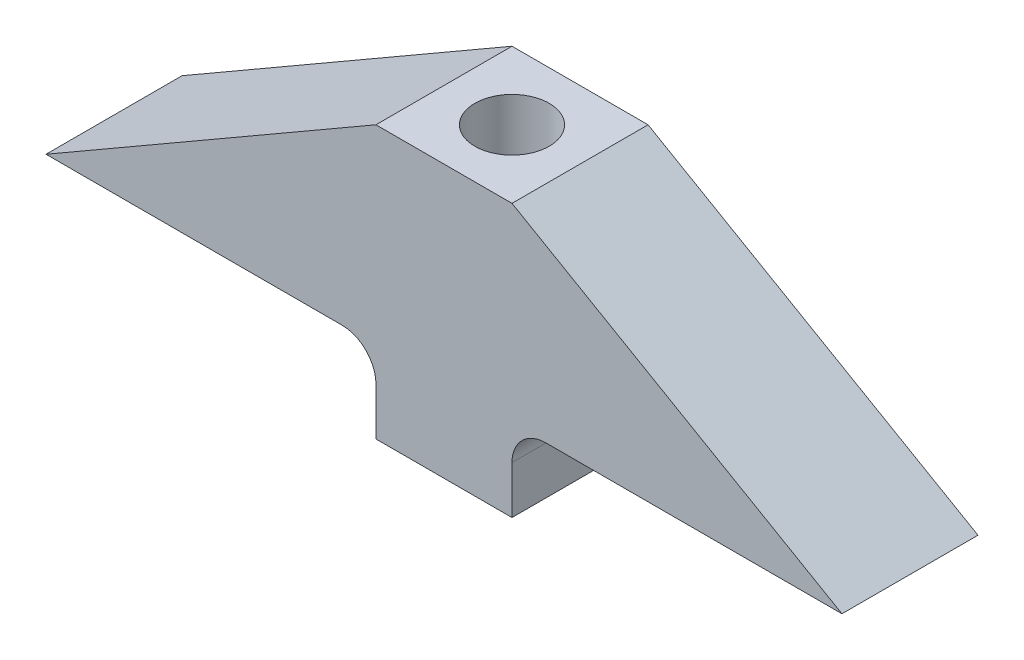
SolidWorks part; units mm, degrees
material "6061-T6 (SS)"
ref_plane "Front Plane" through (0, 0, 0) normal (0, 0, 1) x (1, 0, 0)
ref_plane "Top Plane" through (0, 0, 0) normal (0, 1, 0) x (1, 0, 0)
ref_plane "Right Plane" through (0, 0, 0) normal (1, 0, 0) x (0, 0, -1)
sketch "Sketch1" plane through (0, 0, 0) normal (0, 0, 1) x (1, 0, 0)
  line L0 (0, 0) -> (61.5917, 0)
  line L1 (148.5835, 0) -> (86.9917, 35.56)
  line L2 (86.9917, 35.56) -> (61.5917, 35.56)
  line L3 (61.5917, 35.56) -> (0, 0)
  line L4 (61.5917, 0) -> (61.5917, -15.24)
  line L5 (61.5917, -15.24) -> (86.9917, -15.24)
  line L6 (86.9917, -15.24) -> (86.9917, 0)
  line L7 (86.9917, 0) -> (148.5835, 0)
  point P8 (74.2917, -15.24)
  point P10 (74.2917, 35.56)
  dimension "D1" = 30
  dimension "D2" = 30
  dimension "D3" = 25.4
  dimension "D4" = 35.56
  dimension "D5" = 50.8
  dimension "D6" = 25.4
extrude "Boss-Extrude1" add sketch "Sketch1" along normal blind 25.4
hole_wizard "35/64 (0.54688) Diameter Hole1" positions "Sketch2" profile "Sketch3" hole size "35/64" standard "ANSI Inch"
sketch "Sketch2" plane through (0, 35.56, 0) normal (0, 1, 0) x (1, 0, 0)
  point P0 (74.2917, -12.7)
  dimension "D1" = 12.7
  dimension "D2" = 12.7
sketch "Sketch3" plane through (74.2917, 35.56, 12.7) normal (1, 0, 0) x (0, 0, 1)
  line L0 (0, 0) -> (0, 39.2252)
  line L1 (0, 39.2252) -> (6.9454, 35.052)
  line L2 (6.9454, 35.052) -> (6.9454, 0)
  line L5 (6.9454, 0) -> (0, 0)
  line L10 (0, 39.2252) -> (-6.9454, 35.052) construction
  line L11 (0, -6.35) -> (0, 107.95) construction
  dimension "Hole Dia." = 13.8908
  dimension "Hole Depth" = 35.052
  dimension "Drill Angle" = 118
hole_wizard "#10-32 Tapped Hole1" positions "Sketch4" profile "Sketch5" tap size "#10-32" standard "ANSI Inch"
sketch "Sketch4" plane through (0, -15.24, 0) normal (0, -1, 0) x (-1, 0, 0)
  point P0 (-77.4667, -15.875)
  point P3 (-71.1167, -9.525)
  dimension "D1" = 9.525
  dimension "D2" = 9.525
  dimension "D3" = 9.525
  dimension "D4" = 9.525
sketch "Sketch5" plane through (77.4667, -15.24, 15.875) normal (1, 0, 0) x (0, 0, -1)
  line L0 (0, 0) -> (0, 9.8493)
  line L1 (0, 9.8493) -> (2.0193, 8.636)
  line L2 (2.0193, 8.636) -> (2.0193, 0)
  line L5 (2.0193, 0) -> (0, 0)
  line L10 (0, 9.8493) -> (-2.0193, 8.636) construction
  line L11 (0, -6.35) -> (0, 107.95) construction
  dimension "Tap Drill Dia." = 4.0386
  dimension "Tap Drill Depth" = 8.636
  dimension "Drill Angle" = 118
cosmetic thread "Hole Thread1" parameters "D1"=6.35, "D2"=4.826
cosmetic thread "Hole Thread2" parameters "D1"=6.35, "D2"=4.826
fillet "Fillet1" radius 6.35 2 edges at (86.9917, 0, 12.7) (61.5917, 0, 12.7)
